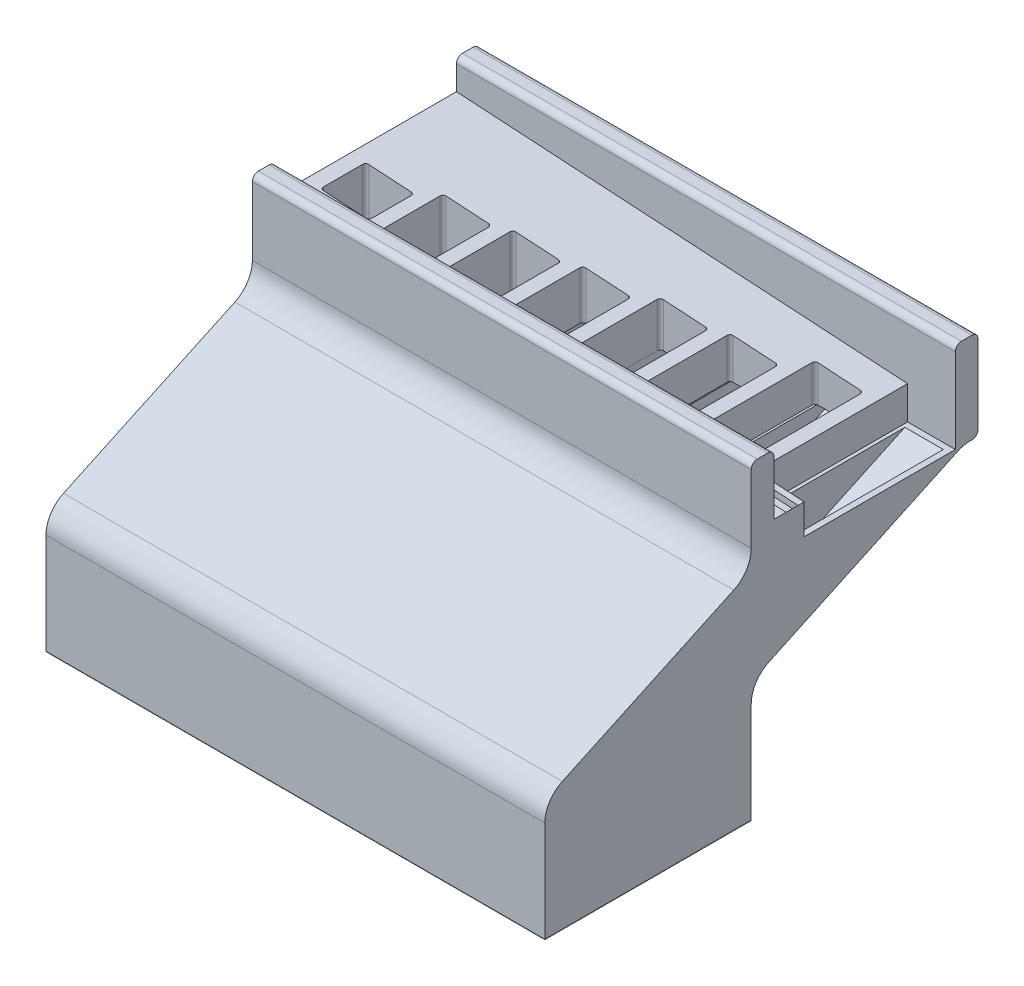
SolidWorks part; units mm, degrees
material "201 Annealed Stainless Steel (SS)"
ref_plane "Front Plane" through (0, 0, 0) normal (0, 0, 1) x (1, 0, 0)
ref_plane "Top Plane" through (0, 0, 0) normal (0, 1, 0) x (1, 0, 0)
ref_plane "Right Plane" through (0, 0, 0) normal (1, 0, 0) x (0, 0, -1)
sketch "Sketch1" plane through (0, 0, 0) normal (0, 0, 1) x (1, 0, 0)
  line L0 (-105.824, 0) -> (103.726, 0)
  line L1 (103.726, 0) -> (103.726, 12.7)
  line L2 (103.726, 12.7) -> (-105.824, 25.4)
  line L3 (-105.824, 25.4) -> (-105.824, 0)
  dimension "D1" = 209.55
  dimension "D2" = 12.7
  dimension "D3" = 25.4
  dimension "D4" = 103.726
extrude "Boss-Extrude1" add sketch "Sketch1" along normal mid plane 76.2
sketch "Sketch2" plane through (0, 0, -38.1) normal (0, 0, -1) x (-1, 0, 0)
  line L0 (-103.726, 0) -> (-103.726, 38.1)
  line L1 (-103.726, 38.1) -> (105.824, 38.1)
  line L2 (105.824, 38.1) -> (105.824, 0)
  line L3 (105.824, 0) -> (-103.726, 0)
  dimension "D1" = 38.1
extrude "Boss-Extrude2" add sketch "Sketch2" along normal blind 9.525 contours L1 L2 L3 L0
mirror "Mirror1" about plane through (0, 0, 0) normal (0, 0, 1) of "Boss-Extrude2"
sketch "Sketch3" plane through (0, 0, 0) normal (0, -1, 0) x (1, 0, 0)
  line L0 (-99.474, 25.4) -> (-99.474, 6.35)
  line L1 (-99.474, 6.35) -> (-79.154, 6.35)
  line L2 (-79.154, 6.35) -> (-79.154, 25.4)
  line L3 (-79.154, 25.4) -> (-99.474, 25.4)
  line L4 (-105.824, 47.625) -> (-105.824, -47.625) construction
  line L5 (-105.824, -47.625) -> (103.726, -47.625) construction
  line L6 (-52.992, 25.4) -> (-73.312, 25.4)
  line L7 (-73.312, 25.4) -> (-73.312, 0)
  line L8 (-73.312, 0) -> (-52.992, 0)
  line L9 (-52.992, 0) -> (-52.992, 25.4)
  line L10 (-26.83, 25.4) -> (-47.15, 25.4)
  line L11 (-47.15, 25.4) -> (-47.15, -3.175)
  line L12 (-47.15, -3.175) -> (-26.83, -3.175)
  line L13 (-26.83, -3.175) -> (-26.83, 25.4)
  line L14 (-0.668, 25.4) -> (-20.988, 25.4)
  line L15 (-20.988, 25.4) -> (-20.988, -6.35)
  line L16 (-20.988, -6.35) -> (-0.668, -6.35)
  line L17 (-0.668, -6.35) -> (-0.668, 25.4)
  line L18 (25.494, 25.4) -> (5.174, 25.4)
  line L19 (5.174, 25.4) -> (5.174, -12.7)
  line L20 (5.174, -12.7) -> (25.494, -12.7)
  line L21 (25.494, -12.7) -> (25.494, 25.4)
  line L22 (51.656, 25.4) -> (31.336, 25.4)
  line L23 (31.336, 25.4) -> (31.336, -15.875)
  line L24 (31.336, -15.875) -> (51.656, -15.875)
  line L25 (51.656, -15.875) -> (51.656, 25.4)
  line L26 (77.818, 25.4) -> (57.498, 25.4)
  line L27 (57.498, 25.4) -> (57.498, -25.4)
  line L28 (57.498, -25.4) -> (77.818, -25.4)
  line L29 (77.818, -25.4) -> (77.818, 25.4)
  line L30 (103.98, 25.4) -> (83.66, 25.4)
  line L31 (83.66, 25.4) -> (83.66, -38.1)
  line L32 (83.66, -38.1) -> (103.98, -38.1)
  line L33 (103.98, -38.1) -> (103.98, 25.4)
  line L35 (103.726, 38.1) -> (-105.824, 38.1) construction
  dimension "D1" = 12.7
  dimension "D2" = 6.35
  dimension "D3" = 26.67
  dimension "D4" = 32.512
  dimension "D6" = 84.836
  dimension "D5" = 58.674
  dimension "D7" = 110.998
  dimension "D8" = 137.16
  dimension "D9" = 163.322
  dimension "D10" = 189.484
  dimension "D11" = 9.525
  dimension "D12" = 22.225
  dimension "D13" = 31.75
  dimension "D14" = 34.925
  dimension "D15" = 41.275
  dimension "D16" = 44.45
  dimension "D17" = 47.625
  dimension "D18" = 53.975
extrude "Cut-Extrude1" cut sketch "Sketch3" against normal through all contours L30 L31 L32 L33
sketch "Sketch6" plane through (1.1465, 18.9169, 0) normal (0.0605, 0.9982, 0) x (0.9982, -0.0605, 0)
  line L0 (-107.1668, -27.94) -> (-107.1668, -33.02)
  line L2 (-107.1668, -38.1) -> (-107.1668, 38.1) construction
  line L3 (-107.1668, -33.02) -> (102.7677, -33.02)
  line L4 (102.7677, -38.1) -> (102.7677, -25.4) construction
  line L5 (102.7677, -33.02) -> (102.7677, -27.94)
  line L6 (-107.1668, -27.94) -> (102.7677, -27.94)
  line L7 (-80.4478, -25.4) -> (-100.8051, -25.4) construction
  dimension "D1" = 2.54
  dimension "D2" = 5.08
extrude "Cut-Extrude2" cut sketch "Sketch6" against normal blind 2.54
fillet "Fillet1" radius 2.54 6 edges at (-1.049, 38.1, -47.625) (-1.049, 38.1, -38.1) (-1.049, 38.1, 38.1) (-1.049, 38.1, 47.625) (-1.049, 0, -47.625) (-1.049, 0, 47.625)
fillet "Fillet2" radius 1.27 29 edges at (-99.474, 12.5076, 25.4) (-79.154, 11.8918, 25.4) (-73.312, 11.7148, 25.4) (-47.15, 10.922, 25.4) (-20.988, 10.1292, 25.4) (5.174, 9.3364, 25.4) (57.498, 7.7508, 25.4) (83.66, 6.9581, 25.4) (31.336, 8.5436, 25.4) (77.818, 7.1351, -25.4) (51.656, 7.9279, -15.875) (25.494, 8.7207, -12.7) (-0.668, 9.5135, -6.35) (-26.83, 10.3062, -3.175) (-52.992, 11.099, 0) (-79.154, 11.8918, 6.35) (77.818, 7.1351, 25.4) (51.656, 7.9279, 25.4) (25.494, 8.7207, 25.4) (-0.668, 9.5135, 25.4) (-26.83, 10.3062, 25.4) (-52.992, 11.099, 25.4) (57.498, 7.7508, -25.4) (31.336, 8.5436, -15.875) (5.174, 9.3364, -12.7) (-20.988, 10.1292, -6.35) (-47.15, 10.922, -3.175) (-73.312, 11.7148, 0) (-99.474, 12.5076, 6.35)
sketch "Sketch8" plane through (103.726, 0, 0) normal (1, 0, 0) x (0, 0, -1)
  line L0 (-45.085, 0) -> (-134.3025, -41.6028)
  line L1 (41.5925, 0) -> (-47.625, -41.6028)
  line L2 (38.1, 0) -> (45.085, 0) construction
  line L3 (-24.13, 0) -> (38.1, 0) construction
  line L4 (-45.085, 0) -> (-25.4, 0) construction
  line L6 (-47.625, 2.54) -> (-47.625, -85.7456) construction
  line L7 (-134.3025, -41.6028) -> (-134.3025, -92.4028)
  line L8 (-134.3025, -92.4028) -> (-47.625, -92.4028)
  line L9 (-47.625, -92.4028) -> (-47.625, -41.6028)
  line L10 (-45.085, 0) -> (41.5925, 0)
  dimension "D1" = 25
  dimension "D2" = 155
  dimension "D3" = 50.8
extrude "Boss-Extrude3" add sketch "Sketch8" against normal up to surface (209.55 mm away) separate body contours L0 L7 L8 L9 L1 L10 up to face at (-105.824, 24.8935, 6.7733)
shell "Shell1" thickness 2.54
ref_plane "Plane1" through (-76.233, 0, 0) normal (-1, 0, 0) x (0, 0, 1)
sketch "Sketch11" plane through (-76.233, 0, 0) normal (-1, 0, 0) x (0, 0, 1)
  line L10 (45.085, 0) -> (-41.5925, 0)
  line L11 (-41.5925, 0) -> (47.625, -41.6028)
  line L12 (45.085, 0) -> (134.3025, -41.6028)
  line L13 (134.3025, -41.6028) -> (134.3025, -92.4028)
  line L14 (134.3025, -92.4028) -> (47.625, -92.4028)
  line L15 (47.625, -92.4028) -> (47.625, -41.6028)
extrude "Boss-Extrude4" add sketch "Sketch11" along normal mid plane 2.54
pattern_linear "LPattern1" count 7 spacing 26.67 along (1, 0, 0) of "Boss-Extrude4"
fillet "Fillet6" radius 12.7 2 edges at (-1.049, -41.6028, 47.625) (-1.049, -41.6028, 134.3025)
fillet "Fillet7" radius 0.508 36 edges at (-90.3935, -92.4028, 131.7625) (-103.284, -92.4028, 90.9637) (-90.3935, -92.4028, 50.165) (-77.503, -92.4028, 90.9637) (-1.049, -92.4028, 47.625) (103.726, -92.4028, 90.9637) (-105.824, -92.4028, 90.9637) (-1.049, -92.4028, 134.3025) (93.1215, -92.4028, 50.165) (101.186, -92.4028, 90.9637) (93.1215, -92.4028, 131.7625) (85.057, -92.4028, 90.9637) (70.452, -92.4028, 50.165) (82.517, -92.4028, 90.9637) (70.452, -92.4028, 131.7625) (58.387, -92.4028, 90.9637) (43.782, -92.4028, 50.165) (55.847, -92.4028, 90.9637) (43.782, -92.4028, 131.7625) (31.717, -92.4028, 90.9637) (17.112, -92.4028, 50.165) (29.177, -92.4028, 90.9637) (17.112, -92.4028, 131.7625) (5.047, -92.4028, 90.9637) (-9.558, -92.4028, 50.165) (2.507, -92.4028, 90.9637) (-9.558, -92.4028, 131.7625) (-21.623, -92.4028, 90.9637) (-36.228, -92.4028, 50.165) (-24.163, -92.4028, 90.9637) (-36.228, -92.4028, 131.7625) (-48.293, -92.4028, 90.9637) (-74.963, -92.4028, 90.9637) (-62.898, -92.4028, 50.165) (-50.833, -92.4028, 90.9637) (-62.898, -92.4028, 131.7625)
fillet "Fillet8" radius 12.7 8 edges at (-90.3935, -43.221, 131.7625) (-62.898, -43.221, 131.7625) (-36.228, -43.221, 131.7625) (-9.558, -43.221, 131.7625) (17.112, -43.221, 131.7625) (43.782, -43.221, 131.7625) (70.452, -43.221, 131.7625) (93.1215, -43.221, 131.7625)
fillet "Fillet9" radius 12.7 7 edges at (-62.898, -39.9846, 50.165) (-36.228, -39.9846, 50.165) (-9.558, -39.9846, 50.165) (17.112, -39.9846, 50.165) (43.782, -39.9846, 50.165) (70.452, -39.9846, 50.165) (93.1215, -39.9846, 50.165)
fillet "Fillet10" radius 12.7 1 edges at (-1.049, 0, 45.085)
fillet "Fillet11" radius 12.7 1 edges at (-1.049, 0, -41.5925)
